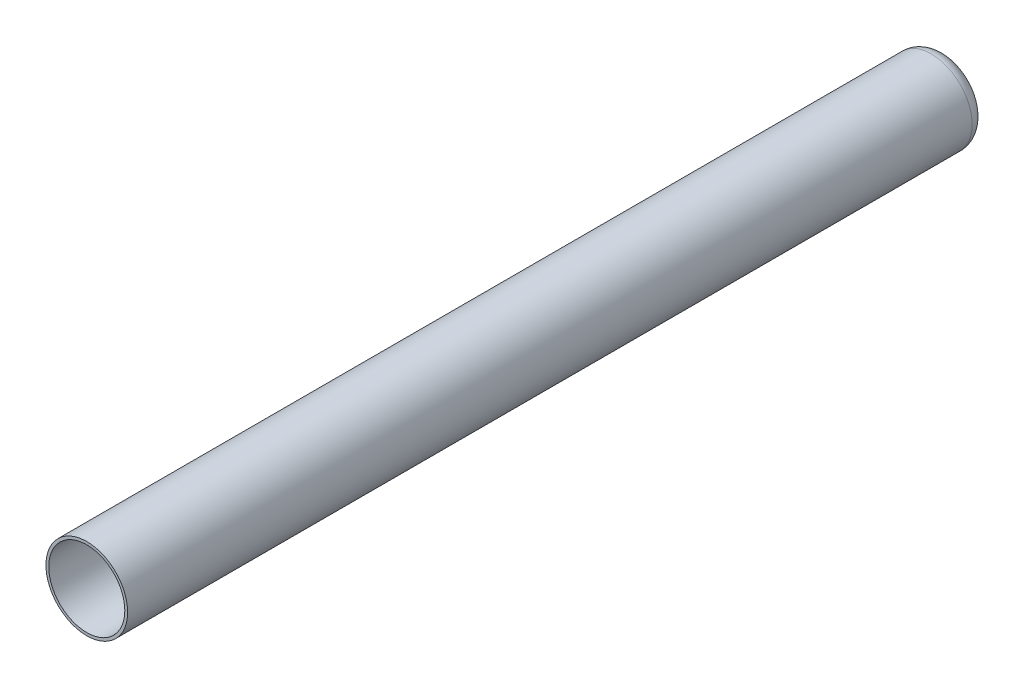
SolidWorks part; units mm, degrees
material "1060 Alloy"
ref_plane "Front Plane" through (0, 0, 0) normal (0, 0, 1) x (1, 0, 0)
ref_plane "Top Plane" through (0, 0, 0) normal (0, 1, 0) x (1, 0, 0)
ref_plane "Right Plane" through (0, 0, 0) normal (1, 0, 0) x (0, 0, -1)
sketch "Sketch1" plane through (0, 0, 0) normal (0, 0, 1) x (1, 0, 0)
  circle A0 centre (0, 0) radius 14.5
  dimension "D1" = 29
extrude "Boss-Extrude1" add sketch "Sketch1" against normal blind 304.8
sketch "Sketch2" plane through (0, 0, 0) normal (0, 0, 1) x (1, 0, 0)
  circle A0 centre (0, 0) radius 13.5
  circle A1 centre (0, 0) radius 14.5 construction
  dimension "D1" = 1
extrude "Cut-Extrude1" cut sketch "Sketch2" against normal offset from surface (301 mm away) 301 up to face at (14.5, 0, 0)
fillet "Fillet2" radius 5 1 edges at (14.5, 0, -304.8)
sketch "Sketch8" plane through (0, 0, -304.8) normal (0, 0, -1) x (-1, 0, 0)
  circle A0 centre (0, 0) radius 9.5
extrude "Cut-Extrude2" cut sketch "Sketch8" against normal blind 10
